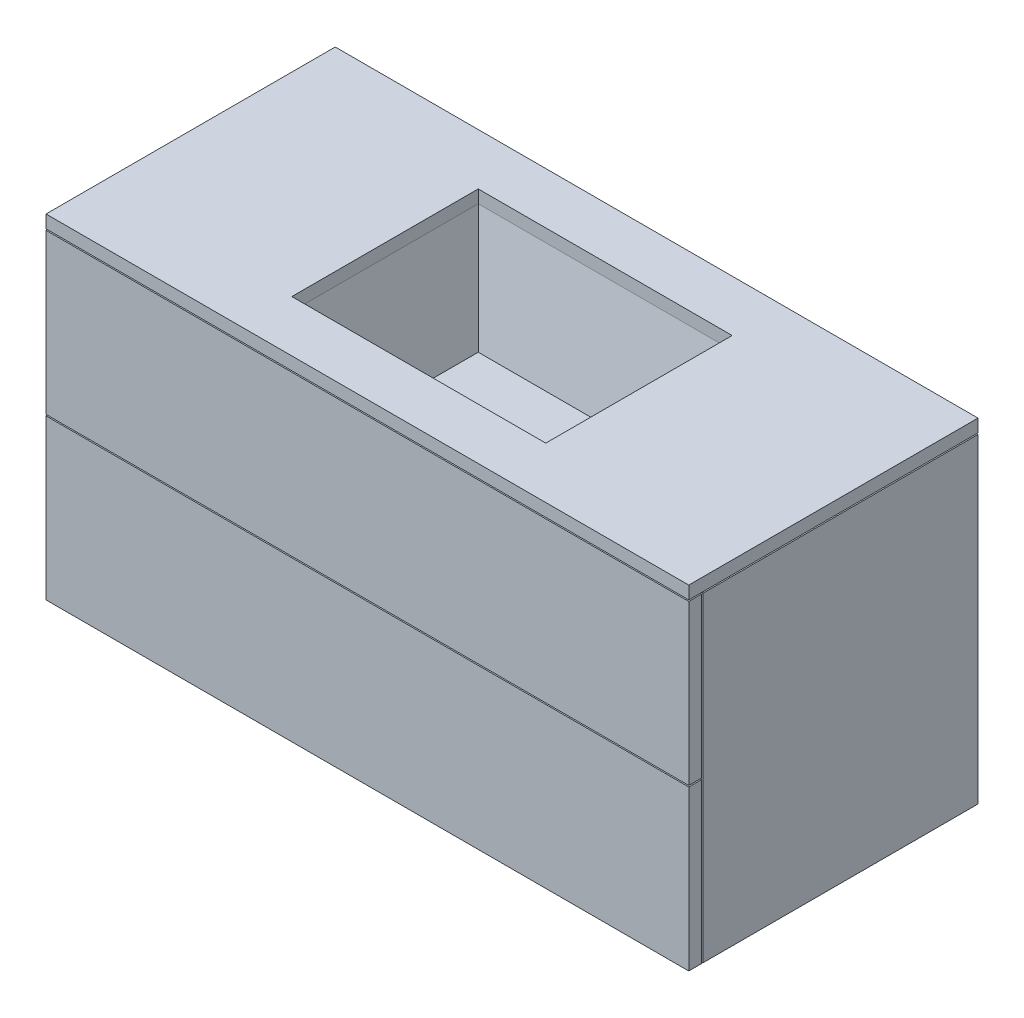
SolidWorks part; units mm, degrees
ref_plane "Спереди" through (0, 0, 0) normal (0, 0, 1) x (1, 0, 0)
ref_plane "Сверху" through (0, 0, 0) normal (0, 1, 0) x (1, 0, 0)
ref_plane "Справа" through (0, 0, 0) normal (1, 0, 0) x (0, 0, -1)
other "Configuration Table"
sketch "Эскиз1" plane through (0, 0, 0) normal (0, 1, 0) x (1, 0, 0)
  line L1 (0, 0) -> (1000, 0)
  line L2 (0, 0) -> (0, 450)
  line L3 (0, 450) -> (1000, 450)
  line L4 (1000, 0) -> (1000, 450)
  dimension "D1" = 1000
  dimension "D2" = 450
extrude "Бобышка-Вытянуть1" add sketch "Эскиз1" along normal blind 520
sketch "Эскиз5" plane through (0, 520, 0) normal (0, 1, 0) x (1, 0, 0)
  line L0 (252.5, 225) -> (0, 225) construction
  line L1 (252.5, 420) -> (747.5, 420)
  line L2 (252.5, 420) -> (252.5, 30)
  line L3 (252.5, 30) -> (747.5, 30)
  line L4 (747.5, 420) -> (747.5, 30)
  line L5 (0, 450) -> (0, 0) construction
  line L6 (500, 420) -> (500, 450) construction
  line L7 (1000, 450) -> (0, 450) construction
  line L8 (747.5, 225) -> (1000, 225) construction
  line L9 (1000, 0) -> (1000, 450) construction
  line L10 (500, 30) -> (500, 0) construction
  line L11 (0, 0) -> (1000, 0) construction
  dimension "D1" = 495
  dimension "D2" = 390
sketch "Эскиз2" plane through (0, 520, 0) normal (0, 1, 0) x (1, 0, 0)
  line L1 (302.5, 370) -> (697.5, 370)
  line L2 (302.5, 370) -> (302.5, 80)
  line L3 (302.5, 80) -> (697.5, 80)
  line L4 (697.5, 370) -> (697.5, 80)
  line L5 (252.5, 420) -> (747.5, 420) construction
  line L6 (252.5, 420) -> (252.5, 30) construction
  line L7 (252.5, 225) -> (302.5, 225) construction
  line L8 (500, 420) -> (500, 370) construction
  dimension "D1" = 50
  dimension "D2" = 50
extrude "Вырез-Вытянуть1" cut sketch "Эскиз2" against normal blind 20
ref_plane "Плоскость1" through (0, 330, 0) normal (0, 1, 0) x (1, 0, 0)
sketch "Эскиз3" plane through (0, 330, 0) normal (0, 1, 0) x (1, 0, 0)
  line L0 (500, 340) -> (500, 370) construction
  line L1 (332.5, 340) -> (667.5, 340)
  line L2 (332.5, 340) -> (332.5, 110)
  line L3 (332.5, 110) -> (667.5, 110)
  line L4 (667.5, 340) -> (667.5, 110)
  line L5 (697.5, 370) -> (302.5, 370) construction
  line L6 (332.5, 225) -> (302.5, 225) construction
  line L7 (302.5, 370) -> (302.5, 80) construction
  dimension "D1" = 30
sketch "Эскиз4" plane through (0, 500, 0) normal (0, 1, 0) x (1, 0, 0)
  line L1 (302.5, 370) -> (697.5, 370)
  line L2 (302.5, 370) -> (302.5, 80)
  line L3 (302.5, 80) -> (697.5, 80)
  line L4 (697.5, 370) -> (697.5, 80)
loft "Вырез-По сечениям1" cut profiles "Эскиз3", "Эскиз4"
sketch "Эскиз8" plane through (0, 0, 0) normal (0, 0, 1) x (1, 0, 0)
  line L0 (0, 520) -> (0, 0) construction
  line L1 (0, 498) -> (1000, 498)
  line L2 (0, 498) -> (0, 500)
  line L3 (0, 500) -> (1000, 500)
  line L4 (1000, 498) -> (1000, 500)
  line L5 (1000, 520) -> (1000, 0) construction
  line L6 (747.5, 520) -> (1000, 520) construction
  line L7 (14.5678, 250) -> (14.5678, 500) construction
  line L8 (0, 250) -> (1000, 250)
  line L9 (0, 250) -> (0, 248)
  line L10 (0, 248) -> (1000, 248)
  line L11 (1000, 250) -> (1000, 248)
  line L12 (14.5678, 250) -> (14.5678, 0) construction
  line L13 (0, 0) -> (1000, 0) construction
  dimension "D1" = 20
  dimension "D2" = 2
  dimension "D3" = 2
extrude "Вырез-Вытянуть2" cut sketch "Эскиз8" against normal blind 20
sketch "Эскиз9" plane through (0, 0, 0) normal (-1, 0, 0) x (0, 0, 1)
  line L0 (-450, 520) -> (-450, 0) construction
  line L1 (-20, 500) -> (-450, 500)
  line L2 (-20, 500) -> (-20, 498)
  line L3 (-22, 498) -> (-450, 498)
  line L4 (-450, 500) -> (-450, 498)
  line L5 (-450, 0) -> (0, 0) construction
  line L6 (-20, 498) -> (-22, 498) construction
  line L7 (-20, 498) -> (-20, 0)
  line L8 (-20, 0) -> (-22, 0)
  line L9 (-22, 498) -> (-22, 0)
extrude "Вырез-Вытянуть3" cut sketch "Эскиз9" against normal blind 20
ref_plane "Плоскость2" through (500, 0, 0) normal (-1, 0, 0) x (0, 0, 1)
mirror "Зеркальное отражение1" about plane through (500, 0, 0) normal (-1, 0, 0) of "Вырез-Вытянуть3"
